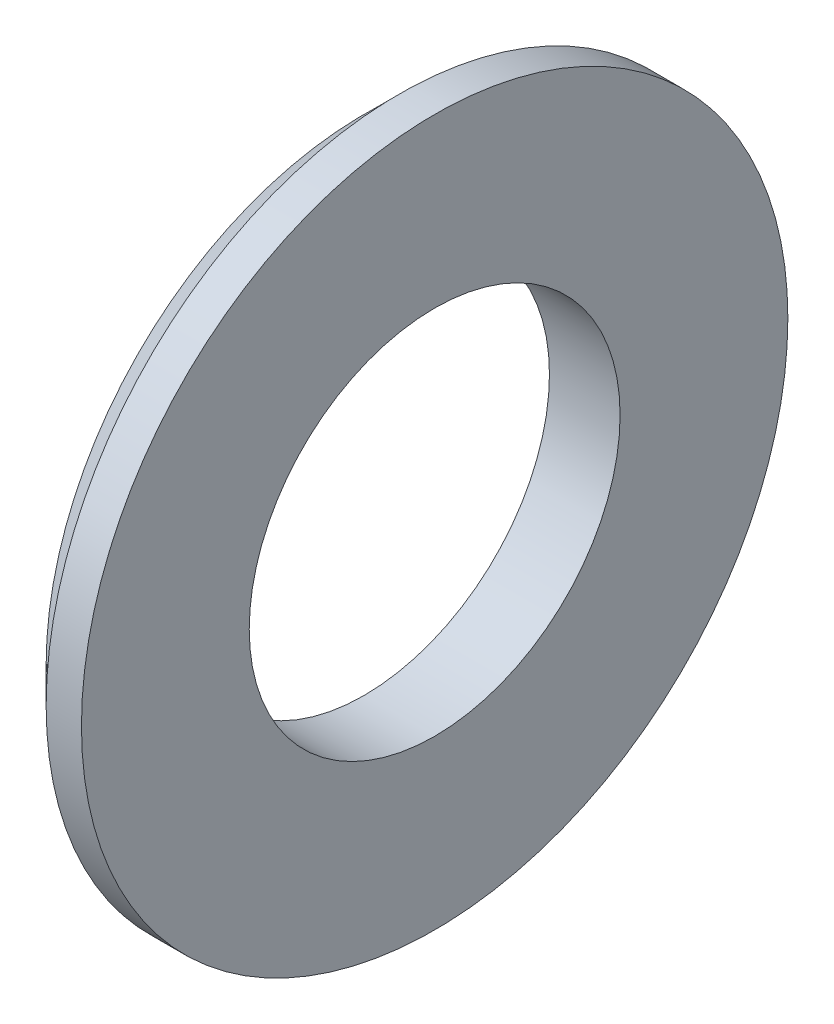
SolidWorks part; units mm, degrees
material "1.0503 (C45)"
ref_plane "Plane1" through (0, 0, 0) normal (0, 0, 1) x (1, 0, 0)
ref_plane "Plane2" through (0, 0, 0) normal (0, 1, 0) x (1, 0, 0)
ref_plane "Plane3" through (0, 0, 0) normal (1, 0, 0) x (0, 0, -1)
other "Configuration Table"
sketch "Sketch1" plane through (0, 0, 0) normal (0, 0, 1) x (1, 0, 0)
  line L0 (-34.925, 0) -> (9.525, 0) construction
  line L1 (0, 5.25) -> (0, 10)
  line L2 (0, 10) -> (-1, 10)
  line L3 (-2, 9) -> (-2, 5.25)
  line L4 (-2, 5.25) -> (0, 5.25)
  line L5 (-2, 9) -> (-1, 10)
  dimension "Inside_dia" = 10.5
  dimension "Outside_dia" = 20
  dimension "Thickness" = 2
  dimension "D2" = 45
  dimension "D3" = 1
revolve "Base-Revolve" add sketch "Sketch1" angle 360 about L0
equation "\"D3@Sketch1\" = \"Thickness@Sketch1\" * .5"
